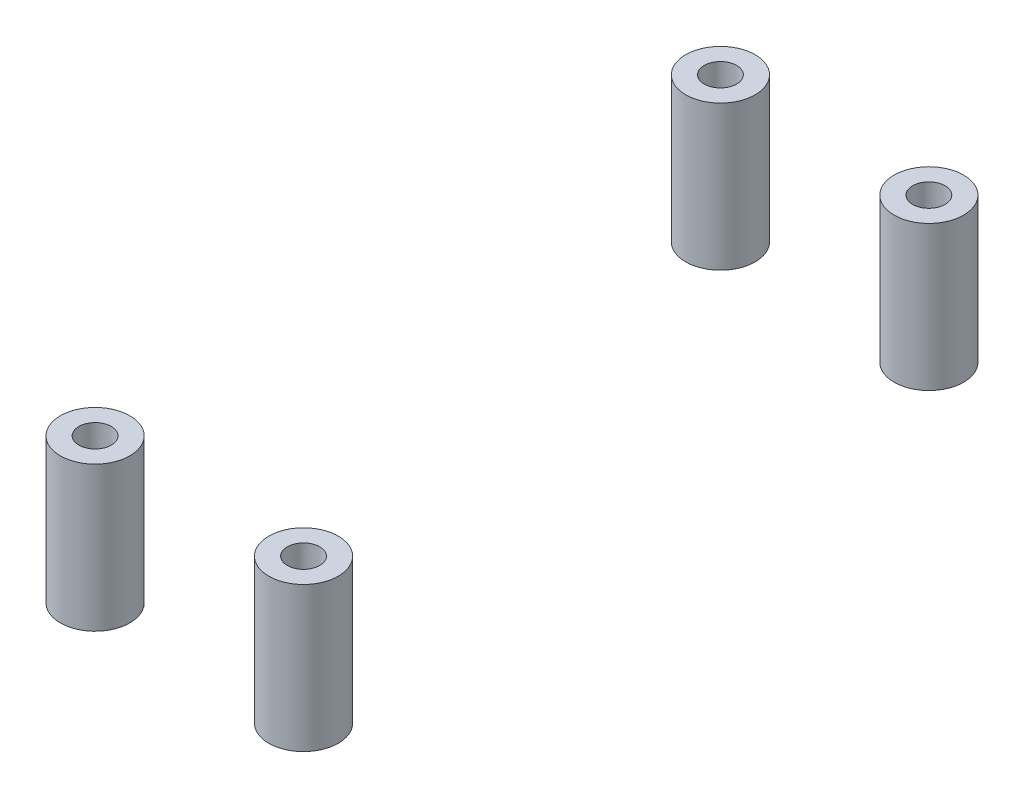
SolidWorks part; units mm, degrees
ref_plane "Front Plane" through (0, 0, 0) normal (0, 0, 1) x (1, 0, 0)
ref_plane "Top Plane" through (0, 0, 0) normal (0, 1, 0) x (1, 0, 0)
ref_plane "Right Plane" through (0, 0, 0) normal (1, 0, 0) x (0, 0, -1)
sketch "Sketch1" plane through (0, 0, 0) normal (0, 1, 0) x (1, 0, 0)
  line L0 (-11.6681, 20.4229) -> (-11.6681, -33.5771) construction
  line L1 (-15.6681, 24.4229) -> (10.3319, 24.4229)
  line L2 (-15.6681, 24.4229) -> (-15.6681, -37.5771)
  line L3 (-15.6681, -37.5771) -> (10.3319, -37.5771)
  line L4 (10.3319, 24.4229) -> (10.3319, -37.5771)
  line L5 (-11.6681, -33.5771) -> (6.3319, -33.5771) construction
  line L6 (40.3319, -48.8271) -> (40.3319, -0.5271) construction
  line L7 (15.3319, 29.4229) -> (-104.6681, 29.4229) construction
  circle A0 centre (6.3319, -33.5771) radius 3
  circle A1 centre (6.3319, 20.4229) radius 3
  circle A2 centre (-11.6681, 20.4229) radius 3
  circle A3 centre (-11.6681, -33.5771) radius 3
  point P12 (-15.6681, -6.5771)
  point P13 (-11.6681, -6.5771)
  point P14 (-2.6681, -37.5771)
  point P15 (-2.6681, -33.5771)
  dimension "D3" = 6
  dimension "D1" = 26
  dimension "D2" = 62
  dimension "D4" = 54
  dimension "D5" = 18
  dimension "D6" = 30
  dimension "D7" = 5
extrude "Boss-Extrude1" add sketch "Sketch1" along normal blind 12.5 contours A3 | A0 | A1 | A2
sketch "Sketch2" plane through (0, 12.5, 0) normal (0, 1, 0) x (1, 0, 0)
  circle A0 centre (-11.6681, 20.4229) radius 1.4
  circle A1 centre (6.3319, 20.4229) radius 1.4
  circle A2 centre (6.3319, -33.5771) radius 1.4
  circle A3 centre (-11.6681, -33.5771) radius 1.4
  dimension "D1" = 2.8
extrude "Cut-Extrude1" cut sketch "Sketch2" against normal blind 10
